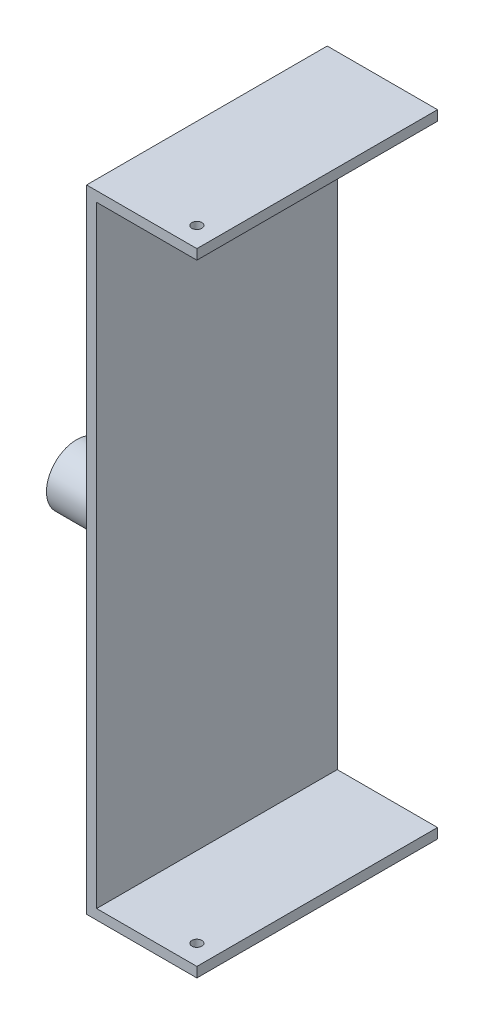
SolidWorks part; units mm, degrees
ref_plane "Front Plane" through (0, 0, 0) normal (0, 0, 1) x (1, 0, 0)
ref_plane "Top Plane" through (0, 0, 0) normal (0, 1, 0) x (1, 0, 0)
ref_plane "Right Plane" through (0, 0, 0) normal (1, 0, 0) x (0, 0, -1)
sketch "Sketch1" plane through (0, 0, 0) normal (0, 0, 1) x (1, 0, 0)
  line L0 (-5, 5) -> (50, 5)
  line L1 (0, 0) -> (50, 0)
  line L2 (0, 0) -> (0, -305)
  line L3 (0, -305) -> (50, -305)
  line L5 (-5, 5) -> (-5, -310)
  line L6 (-5, -310) -> (50, -310)
  line L7 (50, 5) -> (50, 0)
  line L8 (50, -305) -> (50, -310)
  dimension "D1" = 305
  dimension "D3" = 55
  dimension "D2" = 5
extrude "Boss-Extrude1" add sketch "Sketch1" along normal blind 120
sketch "Sketch2" plane through (-5, 0, 0) normal (-1, 0, 0) x (0, 0, 1)
  line L4 (120, 5) -> (120, -310) construction
  circle A0 centre (90, -152.5) radius 15
  point P2 (60, -139.8334)
  point P3 (0, 0)
  point P5 (0, 0)
  point P9 (0, 0)
  point P10 (0, 0)
  point P12 (120, -152.5)
  dimension "D1" = 30
  dimension "D2" = 30
extrude "Boss-Extrude2" add sketch "Sketch2" along normal blind 35
sketch "Sketch3" plane through (0, -310, 0) normal (0, -1, 0) x (1, 0, 0)
  line L0 (50, 120) -> (50, 0) construction
  line L1 (-5, 120) -> (50, 120) construction
  circle A0 centre (40, 110) radius 2.5
  dimension "D1" = 5
  dimension "D2" = 10
  dimension "D3" = 10
extrude "Cut-Extrude1" cut sketch "Sketch3" against normal blind 320
